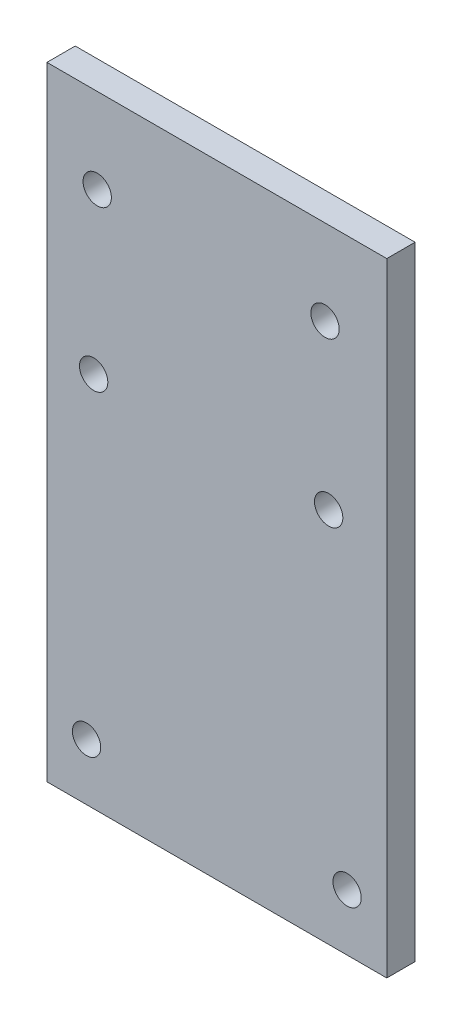
SolidWorks part; units mm, degrees
ref_plane "Front Plane" through (0, 0, 0) normal (0, 0, 1) x (1, 0, 0)
ref_plane "Top Plane" through (0, 0, 0) normal (0, 1, 0) x (1, 0, 0)
ref_plane "Right Plane" through (0, 0, 0) normal (1, 0, 0) x (0, 0, -1)
sketch "Sketch1" plane through (0, 0, 0) normal (0, 0, 1) x (1, 0, 0)
  line L0 (30, -110) -> (30, -83.0444) construction
  line L1 (0, 0) -> (60, 0)
  line L2 (0, 0) -> (0, -110)
  line L3 (0, -110) -> (60, -110)
  line L4 (60, 0) -> (60, -110)
  circle A0 centre (8.8797, -15) radius 2.5
  circle A1 centre (49.0964, -15) radius 2.5
  circle A2 centre (49.7432, -43.54) radius 2.5
  circle A3 centre (8.2522, -43.54) radius 2.5
  circle A4 centre (7, -100) radius 2.5
  circle A5 centre (53, -100) radius 2.5
  dimension "D3" = 5
  dimension "D1" = 60
  dimension "D2" = 110
  dimension "D4" = 7
  dimension "D5" = 10
extrude "Boss-Extrude1" add sketch "Sketch1" along normal blind 5
